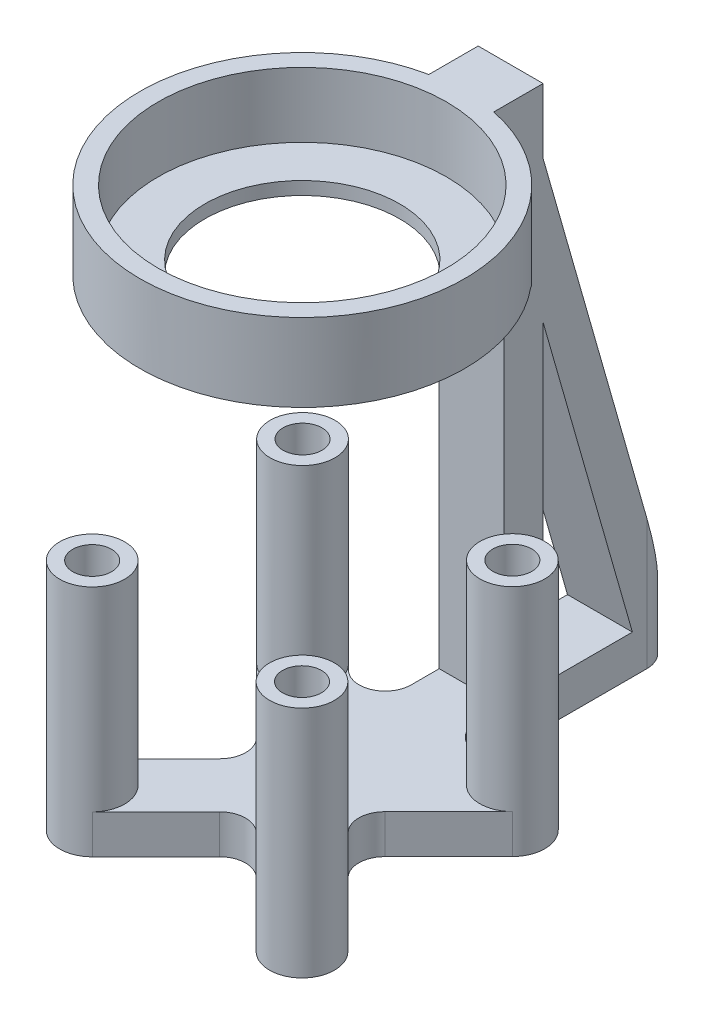
SolidWorks part; units mm, degrees
ref_plane "Спереди" through (0, 0, 0) normal (0, 0, 1) x (1, 0, 0)
ref_plane "Сверху" through (0, 0, 0) normal (0, 1, 0) x (1, 0, 0)
ref_plane "Справа" through (0, 0, 0) normal (1, 0, 0) x (0, 0, -1)
sketch "Эскиз1" plane through (0, 0, 0) normal (0, 1, 0) x (1, 0, 0)
  line L0 (-6.31, -9.8656) -> (0, -3.5399)
  line L5 (-8.08, -8.1) -> (8.08, -8.1) construction
  line L6 (-8.08, -8.1) -> (-8.08, 8.1) construction
  line L7 (-8.08, 8.1) -> (8.08, 8.1) construction
  line L8 (8.08, -8.1) -> (8.08, 8.1) construction
  line L9 (-8.08, -8.1) -> (8.08, 8.1) construction
  line L10 (-8.08, 8.1) -> (8.08, -8.1) construction
  line L11 (-9.85, 6.3344) -> (-3.5312, 0)
  line L12 (-9.85, -6.3344) -> (-3.5312, 0)
  line L13 (-6.31, 9.8656) -> (-2.5, 6.0461)
  line L14 (0, -3.5399) -> (6.31, -9.8656)
  line L15 (-9.85, 6.3344) -> (6.31, -9.8656) construction
  line L16 (2.5, 6.0461) -> (6.31, 9.8656)
  line L17 (-9.85, -6.3344) -> (6.31, 9.8656) construction
  line L18 (3.5312, 0) -> (9.85, 6.3344)
  line L19 (-6.31, -9.8656) -> (9.85, 6.3344) construction
  line L20 (3.5312, 0) -> (9.85, -6.3344)
  line L21 (-6.31, 9.8656) -> (9.85, -6.3344) construction
  line L22 (0, 0) -> (0, 26.0461) construction
  line L24 (-2.5, 6.0461) -> (-2.5, 26.0461)
  line L25 (-2.5, 26.0461) -> (2.5, 26.0461)
  line L26 (2.5, 6.0461) -> (2.5, 26.0461)
  circle A0 centre (-8.08, 8.1) radius 1.5
  circle A1 centre (8.08, 8.1) radius 1.5
  circle A2 centre (-8.08, -8.1) radius 1.5
  circle A3 centre (8.08, -8.1) radius 1.5
  arc A4 (-9.85, 6.3344) -> (-6.31, 9.8656) centre (-8.08, 8.1) cw
  arc A5 (6.31, 9.8656) -> (9.85, 6.3344) centre (8.08, 8.1) cw
  arc A6 (9.85, -6.3344) -> (6.31, -9.8656) centre (8.08, -8.1) cw
  arc A7 (-6.31, -9.8656) -> (-9.85, -6.3344) centre (-8.08, -8.1) cw
  point P0 (0, 0)
  point P28 (0, 16.1325)
  point P32 (0, 0)
  dimension "D3" = 3
  dimension "D1" = 16.2
  dimension "D2" = 16.16
  dimension "D6" = 5
  dimension "D7" = 20
  dimension "D4" = 2.5
  dimension "D5" = 2.5
extrude "Бобышка-Вытянуть1" add sketch "Эскиз1" along normal blind 3
sketch "Эскиз2" plane through (0, 3, 0) normal (0, 1, 0) x (1, 0, 0)
  circle A0 centre (-8.08, -8.1) radius 1.5 construction
  circle A1 centre (8.08, -8.1) radius 1.5 construction
  circle A2 centre (8.08, 8.1) radius 1.5 construction
  circle A3 centre (-8.08, 8.1) radius 1.5 construction
  circle A4 centre (-8.08, -8.1) radius 1.5
  circle A5 centre (8.08, -8.1) radius 1.5
  circle A6 centre (8.08, 8.1) radius 1.5
  circle A7 centre (-8.08, 8.1) radius 1.5
  circle A8 centre (-8.08, -8.1) radius 2.5
  circle A9 centre (-8.08, 8.1) radius 2.5
  circle A10 centre (8.08, 8.1) radius 2.5
  circle A11 centre (8.08, -8.1) radius 2.5
  dimension "D1" = 1
extrude "Бобышка-Вытянуть2" add sketch "Эскиз2" along normal blind 15
sketch "Эскиз3" plane through (0, 3, 0) normal (0, 1, 0) x (1, 0, 0)
  line L0 (-2.5, 26.0461) -> (-2.5, 6.0461) construction
  line L1 (-2.5, 13.0461) -> (2.5, 13.0461)
  line L2 (-2.5, 13.0461) -> (-2.5, 16.0461)
  line L3 (-2.5, 16.0461) -> (2.5, 16.0461)
  line L4 (2.5, 13.0461) -> (2.5, 16.0461)
  line L5 (2.5, 6.0461) -> (2.5, 26.0461) construction
  line L6 (2.5, 26.0461) -> (-2.5, 26.0461) construction
  dimension "D1" = 10
  dimension "D2" = 3
extrude "Бобышка-Вытянуть3" add sketch "Эскиз3" along normal blind 35.0324
sketch "Эскиз4" plane through (2.5, 0, 0) normal (1, 0, 0) x (0, 0, -1)
  line L0 (16.0461, 38.0324) -> (26.0461, 3)
  line L1 (26.0461, 3) -> (22.9263, 3)
  line L2 (16.0461, 3) -> (26.0461, 3) construction
  line L3 (22.9263, 3) -> (16.0461, 27.1029)
  line L4 (16.0461, 38.0324) -> (16.0461, 3) construction
  line L5 (16.0461, 27.1029) -> (16.0461, 38.0324)
  dimension "D1" = 3
extrude "Бобышка-Вытянуть4" add sketch "Эскиз4" against normal up to vertex (5 mm away)
sketch "Эскиз5" plane through (0, 38.0324, 0) normal (0, 1, 0) x (1, 0, 0)
  circle A0 centre (0, 0) radius 7.5
  circle A1 centre (0, 0) radius 12.5
  dimension "D1" = 25
  dimension "D2" = 15
extrude "Бобышка-Вытянуть5" add sketch "Эскиз5" against normal blind 1 separate body
sketch "Эскиз6" plane through (0, 38.0324, 0) normal (0, 1, 0) x (1, 0, 0)
  circle A0 centre (0, 0) radius 11.1
  circle A1 centre (0, 0) radius 12.5
  circle A2 centre (0, 0) radius 12.5
  dimension "D2" = 22.2
  dimension "D1" = 0
extrude "Бобышка-Вытянуть6" add sketch "Эскиз6" along normal blind 5
sketch "Эскиз7" plane through (0, 38.0324, 0) normal (0, 1, 0) x (1, 0, 0)
  line L0 (2.5, 6.0461) -> (2.5, 13.0461) construction
  line L1 (-2.5, 16.0461) -> (2.5, 16.0461)
  line L2 (-2.5, 16.0461) -> (-2.5, 12.2474)
  line L4 (2.5, 16.0461) -> (2.5, 12.2474)
  circle A0 centre (0, 0) radius 12.5 construction
  arc A1 (2.5, 12.2474) -> (-2.5, 12.2474) centre (0, 0) ccw
extrude "Бобышка-Вытянуть7" add sketch "Эскиз7" along normal blind 5 and the other way blind 1
chamfer "Фаска1" distance 5 angle 45 1 edges at (0, 37.0324, -13.0461)
fillet "Скругление1" radius 2 7 edges at (-2.5, 1.5, -26.0461) (2.5, 1.5, -26.0461) (2.5, 1.5, -6.0461) (-2.5, 1.5, -6.0461) (-3.5312, 1.5, 0) (0, 1.5, 3.5399) (3.5312, 1.5, 0)
